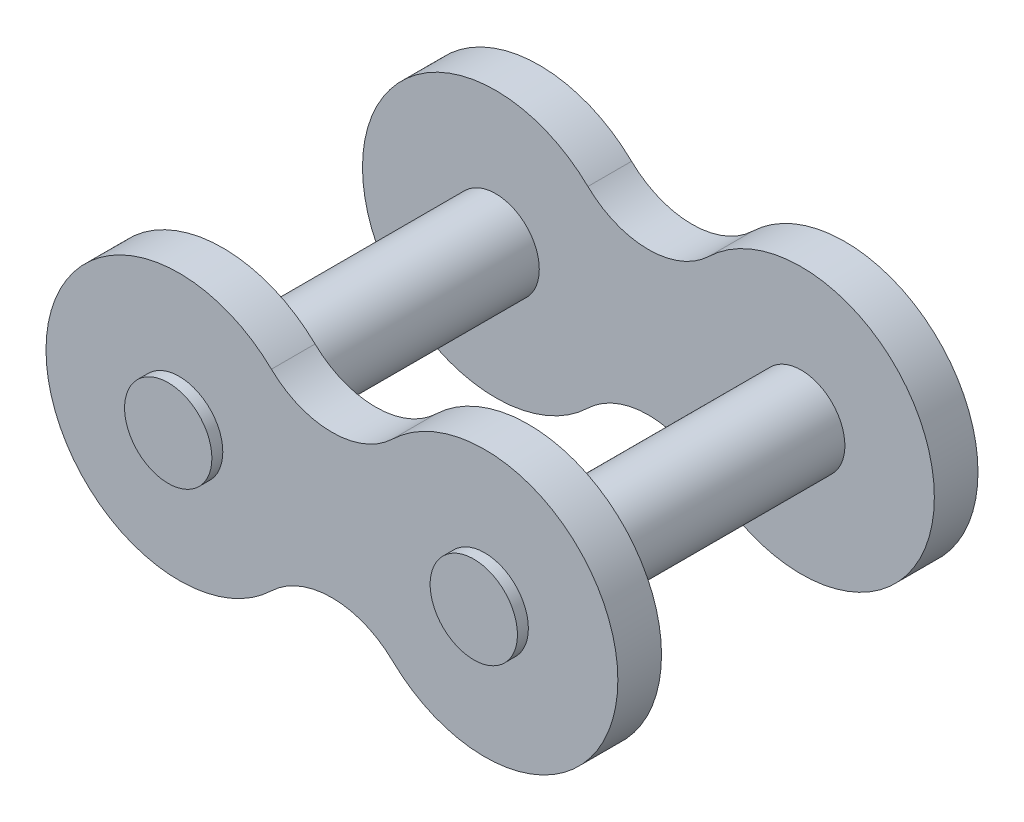
SolidWorks part; units mm, degrees
material "AISI 304"
ref_plane "Alzado" through (0, 0, 0) normal (0, 0, 1) x (1, 0, 0)
ref_plane "Planta" through (0, 0, 0) normal (0, 1, 0) x (1, 0, 0)
ref_plane "Vista lateral" through (0, 0, 0) normal (1, 0, 0) x (0, 0, -1)
sketch "Croquis1" plane through (0, 0, 0) normal (0, 0, 1) x (1, 0, 0)
  line L0 (0, 18.4869) -> (0, 3.2808) construction
  line L1 (-24.1051, 0) -> (21.976, 0) construction
  line L2 (0, -3.2808) -> (0, -17.3193) construction
  arc A0 (-2.7723, 4.3973) -> (-2.7723, -4.3973) centre (-7, 0) ccw
  circle A1 centre (-7, 0) radius 2
  circle A2 centre (7, 0) radius 2
  arc A3 (2.7723, 4.3973) -> (2.7723, -4.3973) centre (7, 0) cw
  arc A4 (-2.7723, 4.3973) -> (2.7723, 4.3973) centre (0, 7.2808) ccw
  arc A5 (-2.7723, -4.3973) -> (2.7723, -4.3973) centre (0, -7.2808) cw
  dimension "D1" = 12.2
  dimension "D2" = 4
  dimension "D4" = 4
  dimension "D3" = 7
extrude "Saliente-Extruir1" add sketch "Croquis1" along normal blind 2
sketch "Croquis3" plane through (0, 0, 2) normal (0, 0, 1) x (1, 0, 0)
  circle A1 centre (-7, 0) radius 2
  circle A2 centre (-7, 0) radius 2
  circle A3 centre (7, 0) radius 2
  circle A4 centre (7, 0) radius 2
  dimension "D1" = 0
  dimension "D2" = 0
extrude "Saliente-Extruir2" add sketch "Croquis3" along normal blind 15 and the other way blind 2.5
ref_plane "Plano1" through (0, 0, 8.25) normal (0, 0, 1) x (1, 0, 0)
mirror "Simetría1" about plane through (0, 0, 8.25) normal (0, 0, 1) of "Saliente-Extruir1"
